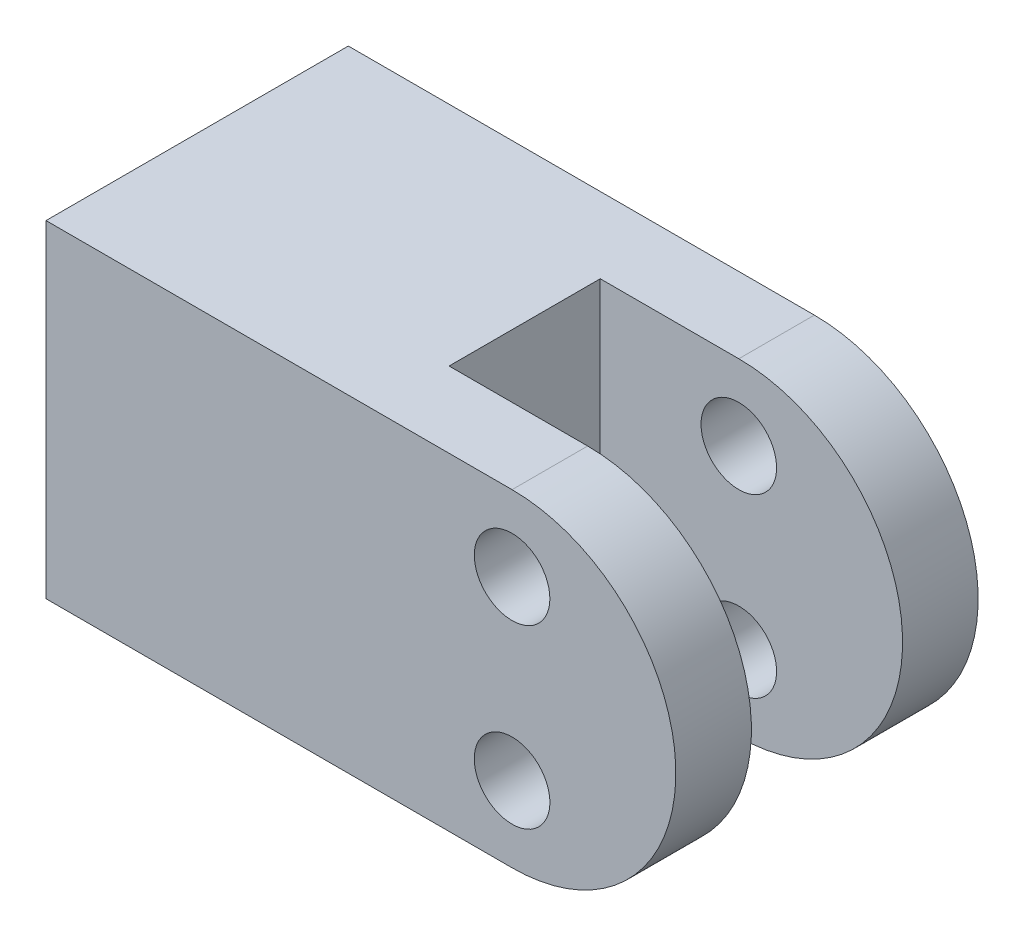
SolidWorks part; units mm, degrees
material "Plain Carbon Steel"
ref_plane "Front Plane" through (0, 0, 0) normal (0, 0, 1) x (1, 0, 0)
ref_plane "Top Plane" through (0, 0, 0) normal (0, 1, 0) x (1, 0, 0)
ref_plane "Right Plane" through (0, 0, 0) normal (1, 0, 0) x (0, 0, -1)
sketch "Sketch1" plane through (0, 0, 0) normal (0, 0, 1) x (1, 0, 0)
  line L0 (0, 0) -> (0, -9333.5188) construction
  line L1 (0, 0) -> (-9333.5188, 0) construction
  line L3 (-18.5, 6.5) -> (0, 6.5)
  line L4 (-18.5, 6.5) -> (-18.5, -6.5)
  line L5 (-18.5, -6.5) -> (0, -6.5)
  line L7 (-18.5, 6.5) -> (0, -6.5) construction
  line L8 (-18.5, -6.5) -> (0, 6.5) construction
  arc A0 (0, 6.5) -> (0, -6.5) centre (0, 0) cw
  circle A1 centre (0, 3.5) radius 1.5
  circle A2 centre (0, -3.5) radius 1.5
  point P5 (-9.25, 0)
  dimension "D3" = 3
  dimension "D1" = 13
  dimension "D2" = 18.5
  dimension "D4" = 3.5
extrude "Boss-Extrude1" add sketch "Sketch1" along normal mid plane 12
sketch "Sketch2" plane through (0, 0, 0) normal (0, 1, 0) x (1, 0, 0)
  line L0 (0, 0) -> (-50000, 0) construction
  line L1 (6.5, -6) -> (6.5, 6) construction
  line L2 (-5.5, 3) -> (6.5, 3)
  line L3 (-5.5, 3) -> (-5.5, -3)
  line L4 (-5.5, -3) -> (6.5, -3)
  line L5 (6.5, 3) -> (6.5, -3)
  line L6 (-5.5, 3) -> (6.5, -3) construction
  line L7 (-5.5, -3) -> (6.5, 3) construction
  point P3 (0.5, 0)
  dimension "D1" = 6
  dimension "D2" = 12
extrude "Cut-Extrude1" cut sketch "Sketch2" against normal through all both and the other way through all
sketch "Sketch3" plane through (-18.5, 0, 0) normal (-1, 0, 0) x (0, 0, 1)
  circle A0 centre (0, 0) radius 2
  dimension "D1" = 4
extrude "Cut-Extrude2" cut sketch "Sketch3" against normal blind 10
cosmetic thread "Cosmetic Thread1" parameters "D2"=5
